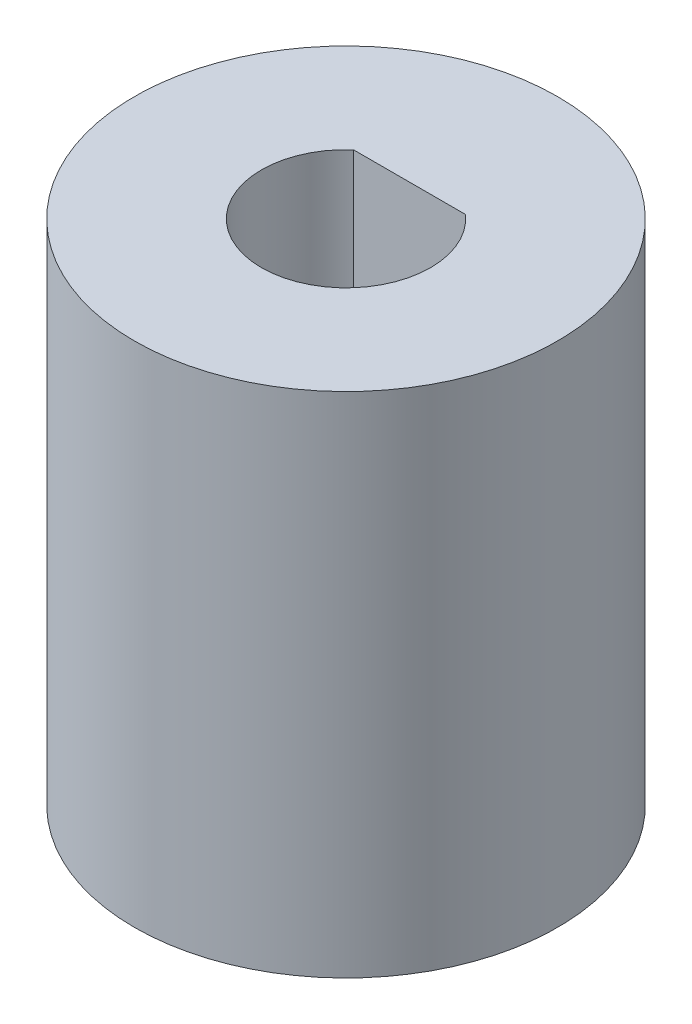
SolidWorks part; units mm, degrees
ref_plane "前视基准面" through (0, 0, 0) normal (0, 0, 1) x (1, 0, 0)
ref_plane "上视基准面" through (0, 0, 0) normal (0, 1, 0) x (1, 0, 0)
ref_plane "右视基准面" through (0, 0, 0) normal (1, 0, 0) x (0, 0, -1)
sketch "Sketch1" plane through (0, 0, 0) normal (0, 1, 0) x (1, 0, 0)
  line L1 (-1.3229, 1.5) -> (1.3229, 1.5)
  circle A0 centre (0, 0) radius 5
  arc A1 (-1.3229, 1.5) -> (1.3229, 1.5) centre (0, 0) ccw
  point P9 (0, 1.5)
extrude "Extrude1" add sketch "Sketch1" along normal blind 12
sketch "Sketch2" plane through (0, 0, -1.5) normal (0, 0, 1) x (1, 0, 0)
  circle A0 centre (0, 5.9968) radius 1
extrude "Extrude2" cut sketch "Sketch2" against normal blind 12
